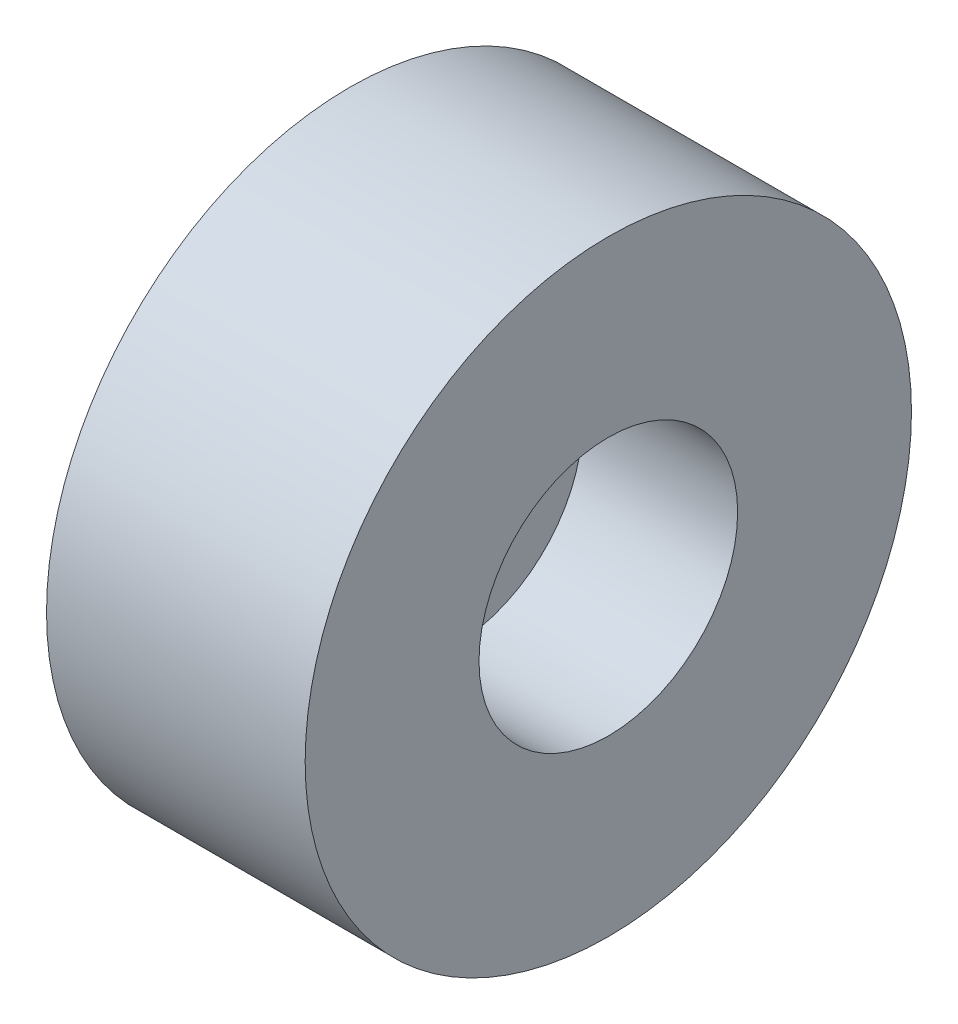
SolidWorks part; units mm, degrees
ref_plane "Plano frontal" through (0, 0, 0) normal (1, 0, 0) x (0, 1, 0)
ref_plane "Plano superior" through (0, 0, 0) normal (0, 0, 1) x (0, 1, 0)
ref_plane "Plano direito" through (0, 0, 0) normal (0, 1, 0) x (-1, 0, 0)
sketch "Esboço2" plane through (0, 0, 0) normal (0, 0, 1) x (0, 1, 0)
  line L1 (-5.8607, 9.9148) -> (-5.8607, 4.9148)
  line L2 (-5.8607, 4.9148) -> (-2.5, 4.9148)
  line L3 (-2.5, 4.9148) -> (-2.5, 7.9148)
  line L4 (-2.5, 7.9148) -> (-1, 7.9148)
  line L8 (-1, 9.9148) -> (-5.8607, 9.9148)
  line L9 (-1, 7.9148) -> (-1, 9.9148)
  line L10 (0, 14.3887) -> (0, -3.1375) construction
  dimension "D1" = 5
  dimension "D2" = 2
  dimension "D3" = 2
  dimension "D4" = 3
revolve "Revolução1" add sketch "Esboço2" angle 360 about L10
